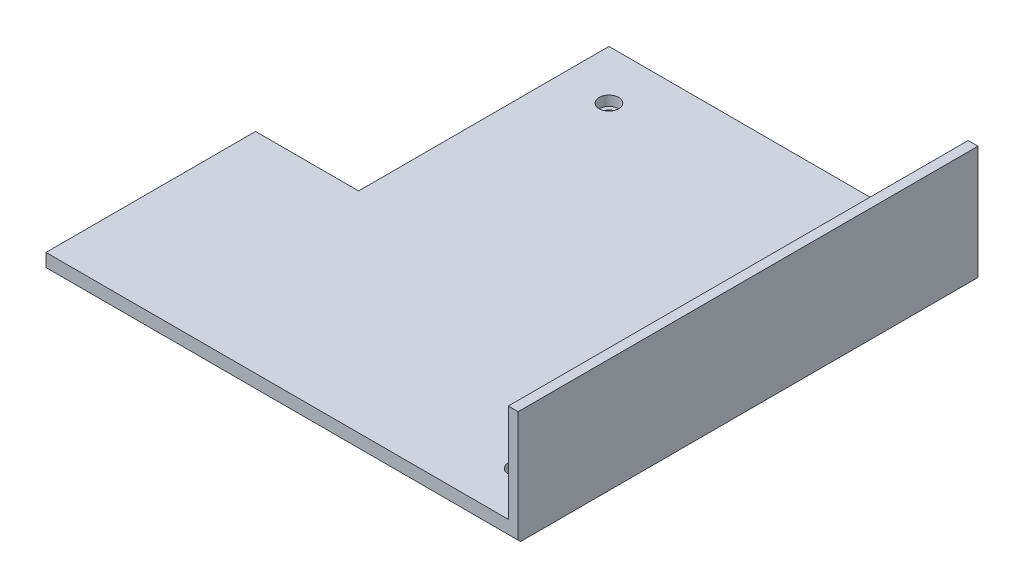
SolidWorks part; units mm, degrees
ref_plane "Front Plane" through (0, 0, 0) normal (0, 0, 1) x (1, 0, 0)
ref_plane "Top Plane" through (0, 0, 0) normal (0, 1, 0) x (1, 0, 0)
ref_plane "Right Plane" through (0, 0, 0) normal (1, 0, 0) x (0, 0, -1)
sketch "Sketch1" plane through (0, 0, 0) normal (0, 1, 0) x (1, 0, 0)
  line L1 (-96.2, 93.7) -> (96.2, 93.7)
  line L2 (-96.2, 93.7) -> (-96.2, -93.7)
  line L3 (-96.2, -93.7) -> (96.2, -93.7)
  line L4 (96.2, 93.7) -> (96.2, -93.7)
  line L5 (-96.2, 93.7) -> (96.2, -93.7) construction
  line L6 (-96.2, -93.7) -> (96.2, 93.7) construction
  point P0 (0, 0)
  dimension "D1" = 187.4
  dimension "D2" = 192.4
extrude "Boss-Extrude1" add sketch "Sketch1" along normal blind 6.35
sketch "Sketch2" plane through (0, 6.35, 0) normal (0, 1, 0) x (1, 0, 0)
  line L2 (-92.2, 89.7) -> (-92.2, -89.7)
  line L4 (96.2, -93.7) -> (96.2, 93.7)
  line L5 (96.2, 93.7) -> (-96.2, 93.7)
  line L6 (-96.2, 93.7) -> (-96.2, -93.7)
  line L7 (-96.2, -93.7) -> (96.2, -93.7)
  line L10 (-96.2, 93.7) -> (-96.2, -93.7)
  line L12 (92.2, 89.7) -> (-92.2, 89.7) construction
  line L13 (96.2, 93.7) -> (-96.2, 93.7) construction
  line L14 (92.2, -89.7) -> (92.2, 89.7) construction
  line L15 (96.2, -93.7) -> (96.2, 93.7) construction
  line L16 (-92.2, 89.7) -> (-92.2, 93.7)
  line L17 (96.2, 93.7) -> (-96.2, 93.7) construction
  line L18 (-92.2, 93.7) -> (-96.2, 93.7)
  line L22 (-92.2, -89.7) -> (92.2, -89.7) construction
  line L23 (-96.2, -93.7) -> (96.2, -93.7) construction
  line L24 (-92.2, -89.7) -> (-92.2, -93.7)
  line L25 (-96.2, -93.7) -> (96.2, -93.7) construction
  line L26 (-92.2, -93.7) -> (-96.2, -93.7)
  dimension "D1" = 0
  dimension "D2" = 4
extrude "Boss-Extrude2" add sketch "Sketch2" along normal blind 40
sketch "Sketch4" plane through (0, 6.35, 0) normal (0, 1, 0) x (1, 0, 0)
  line L0 (-92.2, -93.7) -> (96.2, -93.7) construction
  line L1 (96.2, 93.7) -> (54.2, 93.7)
  line L2 (96.2, 93.7) -> (96.2, -8.3)
  line L3 (96.2, -8.3) -> (54.2, -8.3)
  line L4 (54.2, 93.7) -> (54.2, -8.3)
  line L5 (-96.2, 93.7) -> (-96.2, -93.7) construction
  dimension "D1" = 85.4
  dimension "D2" = 150.4
extrude "Cut-Extrude1" cut sketch "Sketch4" against normal up to next
sketch "Sketch5" plane through (0, 6.35, 0) normal (0, 1, 0) x (1, 0, 0)
  line L0 (-96.2, 93.7) -> (-96.2, -93.7) construction
  line L1 (54.2, 93.7) -> (-96.2, 93.7) construction
  line L2 (54.2, 93.7) -> (54.2, 53.7) construction
  line L3 (54.2, 53.7) -> (-96.2, 53.7) construction
  line L4 (-96.2, 93.7) -> (-96.2, 53.7) construction
  line L5 (-92.2, -93.7) -> (96.2, -93.7) construction
  line L6 (-96.2, 93.7) -> (-56.2, 93.7) construction
  line L7 (-96.2, 93.7) -> (-96.2, -93.7) construction
  line L8 (-96.2, -93.7) -> (-56.2, -93.7) construction
  line L9 (-56.2, 93.7) -> (-56.2, -93.7) construction
  line L10 (-76.2, -93.7) -> (-76.2, 93.7) construction
  line L11 (54.2, 73.7) -> (-96.2, 73.7) construction
  point P18 (-76.2, 73.7)
  point P20 (-76.2, -73.7)
  point P24 (34.2, 73.7)
  dimension "D1" = 40
  dimension "D2" = 40
  dimension "D3" = 20
  dimension "D4" = 20
hole_wizard "CBORE for M4 SHCS1" positions "Sketch5" profile "Sketch6" counterbore size "M4" standard "ANSI Metric" end condition up to next
sketch "Sketch6" plane through (34.2, 6.35, -73.7) normal (1, 0, 0) x (0, 0, 1)
  line L0 (0, 0) -> (0, 6.35)
  line L1 (0, 6.35) -> (2.25, 6.35)
  line L3 (2.25, 6.35) -> (2.25, 4)
  line L4 (2.25, 4) -> (4, 4)
  line L5 (4, 4) -> (4, 0)
  line L7 (4, 0) -> (0, 0)
  line L11 (0, -6.35) -> (0, 107.95) construction
  dimension "Thru Hole Dia." = 4.5
  dimension "Thru Hole Depth" = 6.35
  dimension "C'Bore Dia." = 8
  dimension "C'Bore Depth" = 4
mirror "Mirror1" about plane through (96.2, 6.35, -93.7) normal (-1, 0, 0) of bodies 105
delete or keep bodies "Body-Delete/Keep 1" type delete bodies bodies 105
chamfer "Chamfer1" distance 1 angle 45 2 edges at (192.4, 0, 93.7) (96.2, 0, 51)
equation "\"D2@Sketch1\"=384.8/2"
equation "\"D2@Sketch4\"=152.4-2"
equation "\"D1@Sketch4\"=87.4-2"
